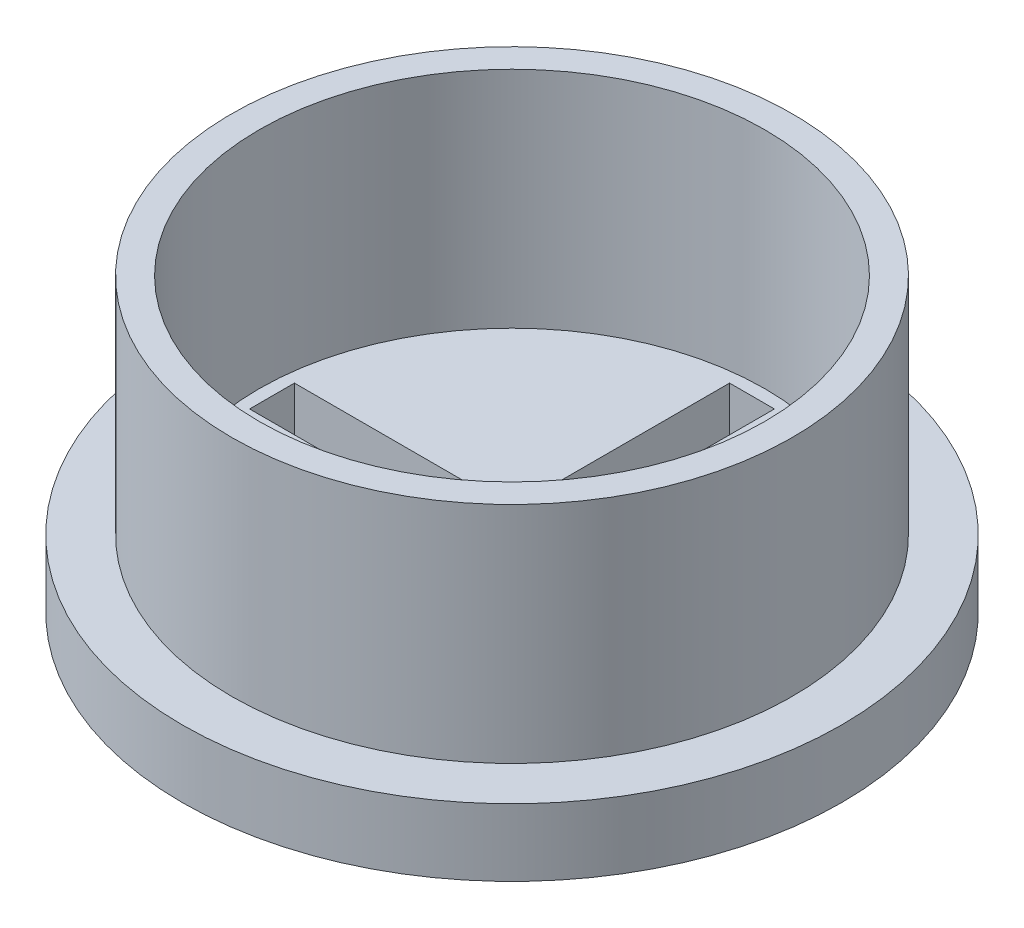
SolidWorks part; units mm, degrees
ref_plane "Front Plane" through (0, 0, 0) normal (0, 0, 1) x (1, 0, 0)
ref_plane "Top Plane" through (0, 0, 0) normal (0, 1, 0) x (1, 0, 0)
ref_plane "Right Plane" through (0, 0, 0) normal (1, 0, 0) x (0, 0, -1)
sketch "Sketch1" plane through (0, 0, 0) normal (0, 1, 0) x (1, 0, 0)
  circle A0 centre (0, 0) radius 14.7
  dimension "D1" = 29.4
extrude "Boss-Extrude1" add sketch "Sketch1" along normal blind 3
sketch "Sketch3" plane through (0, 3, 0) normal (0, 1, 0) x (1, 0, 0)
  line L1 (-10.7, 1) -> (10.7, 1)
  line L2 (-10.7, 1) -> (-10.7, -1)
  line L3 (-10.7, -1) -> (10.7, -1)
  line L4 (10.7, 1) -> (10.7, -1)
  line L5 (-10.7, 1) -> (10.7, -1) construction
  line L6 (-10.7, -1) -> (10.7, 1) construction
  point P0 (0, 0)
  dimension "D1" = 2
  dimension "D2" = 21.4
extrude "Cut-Extrude1" cut sketch "Sketch3" against normal blind 3 contours L3 L4 L1 L2
sketch "Sketch4" plane through (0, 3, 0) normal (0, 1, 0) x (1, 0, 0)
  line L1 (-1, 10.7) -> (1, 10.7)
  line L2 (-1, 10.7) -> (-1, -10.7)
  line L3 (-1, -10.7) -> (1, -10.7)
  line L4 (1, 10.7) -> (1, -10.7)
  line L5 (-1, 10.7) -> (1, -10.7) construction
  line L6 (-1, -10.7) -> (1, 10.7) construction
  point P0 (0, 0)
  dimension "D1" = 2
  dimension "D2" = 21.4
extrude "Cut-Extrude2" cut sketch "Sketch4" against normal blind 3
sketch "Sketch5" plane through (0, 3, 0) normal (0, 1, 0) x (1, 0, 0)
  circle A0 centre (0, 0) radius 12.5
  dimension "D1" = 25
extrude "Boss-Extrude3" add sketch "Sketch5" along normal blind 10
sketch "Sketch6" plane through (0, 13, 0) normal (0, 1, 0) x (1, 0, 0)
  circle A0 centre (0, 0) radius 11.27
  dimension "D1" = 22.54
extrude "Cut-Extrude3" cut sketch "Sketch6" against normal blind 10
